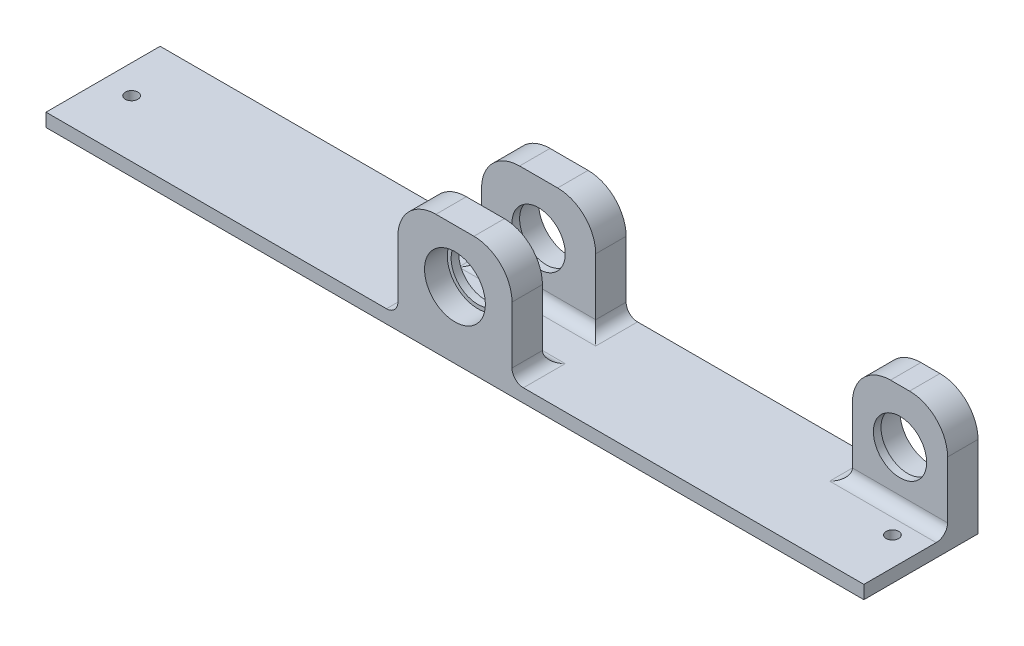
SolidWorks part; units mm, degrees
ref_plane "Front Plane" through (0, 0, 0) normal (0, 0, 1) x (1, 0, 0)
ref_plane "Top Plane" through (0, 0, 0) normal (0, 1, 0) x (1, 0, 0)
ref_plane "Right Plane" through (0, 0, 0) normal (1, 0, 0) x (0, 0, -1)
sketch "Sketch2" plane through (0, 0, 0) normal (0, 1, 0) x (1, 0, 0)
  line L1 (107.5, 15) -> (-107.5, 15)
  line L2 (107.5, 15) -> (107.5, -15)
  line L3 (107.5, -15) -> (-107.5, -15)
  line L4 (-107.5, 15) -> (-107.5, -15)
  line L5 (107.5, 15) -> (-107.5, -15) construction
  line L6 (107.5, -15) -> (-107.5, 15) construction
  point P0 (0, 0)
  dimension "D1" = 215
  dimension "D2" = 30
extrude "Boss-Extrude1" add sketch "Sketch2" along normal blind 3.5
sketch "HOLES TBD" plane through (0, 3.5, 0) normal (0, 1, 0) x (1, 0, 0)
  line L0 (100, 0) -> (-100, 0) construction
  circle A0 centre (-100, 0) radius 1.65
  circle A1 centre (100, 0) radius 1.65
  point P4 (0, 0)
  dimension "D2" = 3.3
  dimension "D1" = 200
sketch "Sketch4" plane through (0, 3.5, 0) normal (0, 1, 0) x (1, 0, 0)
  line L0 (-107.5, -15) -> (107.5, -15) construction
  line L7 (-15, -15) -> (15, -15)
  line L8 (-15, -15) -> (-15, -7)
  line L9 (-15, -7) -> (15, -7)
  line L10 (15, -15) -> (15, -7)
  line L11 (-15, -15) -> (15, -7) construction
  line L12 (-15, -7) -> (15, -15) construction
  line L13 (0, 0) -> (0, -15) construction
  line L14 (-100, 0) -> (100, 0) construction
  line L15 (-15, 7) -> (15, 15) construction
  line L16 (-15, 15) -> (15, 7) construction
  line L18 (107.5, 15) -> (82.5, 15)
  line L19 (15, 15) -> (15, 7)
  line L20 (-15, 7) -> (15, 7)
  line L21 (-15, 15) -> (-15, 7)
  line L22 (-15, 15) -> (15, 15)
  line L27 (107.5, 15) -> (107.5, 7)
  line L28 (107.5, 7) -> (82.5, 7)
  line L29 (82.5, 15) -> (82.5, 7)
  point P10 (0, -11)
  point P28 (0, 11)
  dimension "D1" = 8
  dimension "D2" = 8
  dimension "D3" = 30
  dimension "D4" = 25
extrude "Boss-Extrude2" add sketch "Sketch4" along normal blind 28
hole_wizard "CBORE for M6 Hex Head Bolt1" positions "3DSketch2" profile "Sketch6" counterbore size "M6" standard "ANSI Metric" end condition up to next
sketch3d "3DSketch2"
  line L0 (-107.5, 0, 15) -> (107.5, 0, 15) construction
  line L1 (15, 31.5, 15) -> (15, 3.5, 15) construction
  line L2 (107.5, 0, -15) -> (-107.5, 0, -15) construction
  line L3 (15, 31.5, -15) -> (15, 3.5, -15) construction
  point P0 (0, 17.5, 15)
  point P7 (0, 17.5, -15)
  point P9 (95, 17.5, -15)
  dimension "D1" = 17.5
  dimension "D2" = 15
  dimension "D3" = 17.5
  dimension "D4" = 15
  dimension "D5" = 17.5
  dimension "D6" = 95
sketch "Sketch6" plane through (0, 17.5, 15) normal (1, 0, 0) x (0, -1, 0)
  line L0 (0, 0) -> (0, 8)
  line L1 (0, 8) -> (7, 8)
  line L3 (7, 8) -> (7, 6)
  line L4 (7, 6) -> (8, 6)
  line L5 (8, 6) -> (8, 0)
  line L7 (8, 0) -> (0, 0)
  line L11 (0, -6.35) -> (0, 107.95) construction
  dimension "Thru Hole Dia." = 14
  dimension "Thru Hole Depth" = 8
  dimension "C'Bore Dia." = 16
  dimension "C'Bore Depth" = 6
fillet "Fillet1" radius 10 6 edges at (-15, 31.5, 11) (-15, 31.5, -11) (15, 31.5, -11) (15, 31.5, 11) (107.5, 31.5, -11) (82.5, 31.5, -11)
extrude "Cut-Extrude1" cut sketch "HOLES TBD" against normal through all
fillet "Fillet2" radius 3 8 edges at (15, 3.5, 11) (15, 3.5, -11) (-15, 3.5, 11) (-15, 3.5, -11) (0, 3.5, 7) (0, 3.5, -7) (82.5, 3.5, -11) (95, 3.5, -7)
